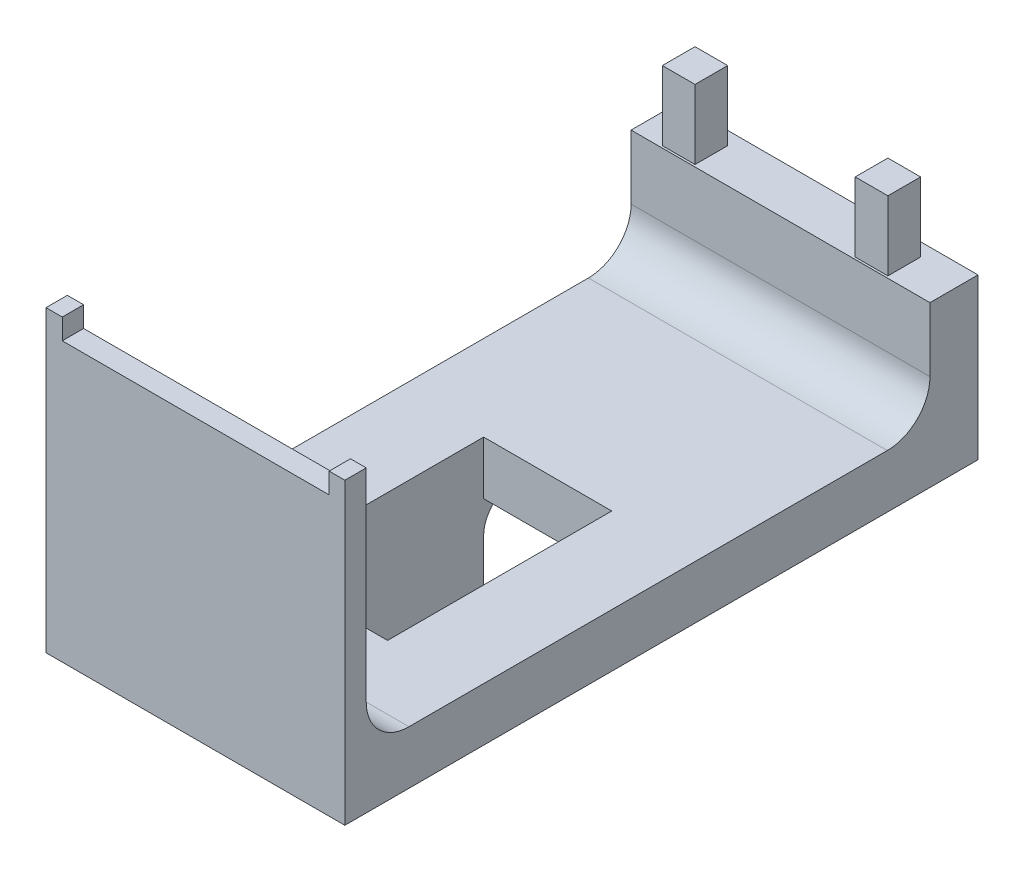
SolidWorks part; units mm, degrees
ref_plane "Front Plane" through (0, 0, 0) normal (0, 0, 1) x (1, 0, 0)
ref_plane "Top Plane" through (0, 0, 0) normal (0, 1, 0) x (1, 0, 0)
ref_plane "Right Plane" through (0, 0, 0) normal (1, 0, 0) x (0, 0, -1)
sketch "Sketch1" plane through (0, 0, 0) normal (0, 1, 0) x (1, 0, 0)
  line L1 (0, 0) -> (27.998, 0)
  line L3 (0, 4.5) -> (27.998, 4.5)
  line L5 (27.998, 4.5) -> (0, 4.5)
  line L9 (27.998, 0) -> (0, 0)
  line L10 (27.998, 0) -> (27.998, 4.5)
  line L11 (27.998, 4.5) -> (0, 4.5)
  line L12 (0, 0) -> (0, 4.5)
  dimension "D1" = 27.998
  dimension "D2" = 4.5
extrude "Boss-Extrude2" add sketch "Sketch1" along normal blind 15 contours L12 L1 L10 L3
sketch "Sketch2" plane through (0, 0, 0) normal (0, 0, 1) x (1, 0, 0)
  line L0 (0, 15) -> (0, 0) construction
  line L1 (27.998, 0) -> (0, 0)
  line L2 (27.998, 0) -> (27.998, 5)
  line L3 (27.998, 5) -> (0, 5)
  line L4 (0, 0) -> (0, 5)
  dimension "D1" = 5
extrude "Boss-Extrude3" add sketch "Sketch2" along normal blind 52.81
fillet "Fillet1" radius 4 1 edges at (13.999, 5, 0)
sketch "Sketch3" plane through (0, 0, 52.81) normal (0, 0, 1) x (1, 0, 0)
  line L0 (1.524, 244.0697) -> (1.524, 26.0697) construction
  line L1 (27.998, 0) -> (0, 0)
  line L2 (27.998, 0) -> (27.998, 28)
  line L3 (27.998, 28) -> (0, 28)
  line L4 (0, 0) -> (0, 28)
  line L5 (1.524, 26.0697) -> (26.524, 26.0697) construction
  line L6 (26.524, 26.0697) -> (26.524, 244.0697) construction
  line L7 (1.524, 244.0697) -> (1.524, 26.0697)
  line L8 (1.524, 26.0697) -> (26.524, 26.0697)
  line L9 (26.524, 26.0697) -> (26.524, 244.0697)
  line M5 (27.998, 0) -> (27.998, 5)
  line M6 (27.998, 5) -> (0, 5)
  line M7 (0, 5) -> (0, 0)
  line M8 (0, 0) -> (27.998, 0)
  dimension "D1" = 28
extrude "Boss-Extrude4" add sketch "Sketch3" along normal up to surface (2 mm away) contours L9 L8 L7 L3 L4 L2 M6 | M8 M5 M6 M7
fillet "Fillet2" radius 4 1 edges at (13.999, 5, 52.81)
sketch "Sketch4" plane through (0, 15, 0) normal (0, 1, 0) x (1, 0, 0)
  line L0 (2.478, 3.51) -> (2.478, -0.052) construction
  line L1 (6.04, -0.052) -> (6.04, 3.51) construction
  line L2 (6.04, 3.51) -> (2.478, 3.51) construction
  line L3 (2.478, -0.052) -> (6.04, -0.052) construction
  line L4 (24.11, 3.51) -> (24.11, -0.052) construction
  line L5 (24.11, -0.052) -> (20.546, -0.052) construction
  line L6 (20.546, -0.052) -> (20.546, 3.51) construction
  line L7 (20.546, 3.51) -> (24.11, 3.51) construction
  line L8 (2.478, 3.51) -> (2.478, -0.052)
  line L9 (6.04, -0.052) -> (6.04, 3.51)
  line L10 (6.04, 3.51) -> (2.478, 3.51)
  line L11 (2.478, -0.052) -> (6.04, -0.052)
  line L12 (24.11, 3.51) -> (24.11, -0.052)
  line L13 (24.11, -0.052) -> (20.546, -0.052)
  line L14 (20.546, -0.052) -> (20.546, 3.51)
  line L15 (20.546, 3.51) -> (24.11, 3.51)
  line L20 (20.796, 3.26) -> (23.86, 3.26)
  line L21 (23.86, 3.26) -> (23.86, 0.198)
  line L22 (23.86, 0.198) -> (20.796, 0.198)
  line L23 (20.796, 0.198) -> (20.796, 3.26)
  line L24 (5.79, 0.198) -> (5.79, 3.26)
  line L25 (5.79, 3.26) -> (2.728, 3.26)
  line L26 (2.728, 3.26) -> (2.728, 0.198)
  line L27 (2.728, 0.198) -> (5.79, 0.198)
  dimension "D1" = 0.25
extrude "Boss-Extrude5" add sketch "Sketch4" along normal blind 6.5 contours L23 L22 L21 L20 | L26 L27 L24 L25
sketch "Sketch5" plane through (0, 0, 0) normal (0, -1, 0) x (1, 0, 0)
  line L0 (27.998, 54.81) -> (27.998, -4.5) construction
  line L1 (7.998, 42.81) -> (19.998, 42.81)
  line L2 (7.998, 42.81) -> (7.998, 21.81)
  line L3 (7.998, 21.81) -> (19.998, 21.81)
  line L4 (19.998, 42.81) -> (19.998, 21.81)
  line L5 (0, 54.81) -> (0, -4.5) construction
  line L6 (0, 54.81) -> (27.998, 54.81) construction
  dimension "D1" = 12
  dimension "D2" = 21
  dimension "D3" = 8
  dimension "D4" = 7.998
  dimension "D5" = 12
extrude "Cut-Extrude1" cut sketch "Sketch5" against normal blind 6.5 contours L1 L4 L3 L2
sketch "Sketch6" plane through (0, 0, 0) normal (0, -1, 0) x (1, 0, 0)
  line L1 (7.998, 42.81) -> (4.998, 42.81)
  line L2 (7.998, 42.81) -> (7.998, 21.81)
  line L3 (7.998, 21.81) -> (4.998, 21.81)
  line L4 (4.998, 42.81) -> (4.998, 21.81)
  dimension "D1" = 3
extrude "Boss-Extrude6" add sketch "Sketch6" along normal blind 12.2
sketch "Sketch7" plane through (4.998, 0, 0) normal (-1, 0, 0) x (0, 0, 1)
  arc A0 (24.81, -7.65) -> (24.81, -10.75) centre (24.81, -9.2) ccw construction
  arc A1 (24.81, -10.75) -> (24.81, -7.65) centre (24.81, -9.2) ccw construction
  arc A2 (39.81, -7.65) -> (39.81, -10.75) centre (39.81, -9.2) ccw construction
  arc A3 (39.81, -10.75) -> (39.81, -7.65) centre (39.81, -9.2) ccw construction
  arc A4 (24.81, -7.65) -> (24.81, -10.75) centre (24.81, -9.2) ccw
  arc A5 (24.81, -10.75) -> (24.81, -7.65) centre (24.81, -9.2) ccw
  arc A6 (39.81, -7.65) -> (39.81, -10.75) centre (39.81, -9.2) ccw
  arc A7 (39.81, -10.75) -> (39.81, -7.65) centre (39.81, -9.2) ccw
extrude "Cut-Extrude2" cut sketch "Sketch7" against normal blind 12.2
fillet "Fillet4" radius 3 2 edges at (6.498, -12.2, 21.81) (6.498, -12.2, 42.81)
fillet "Fillet5" radius 3 2 edges at (6.498, 0, 42.81) (6.498, 0, 21.81)
